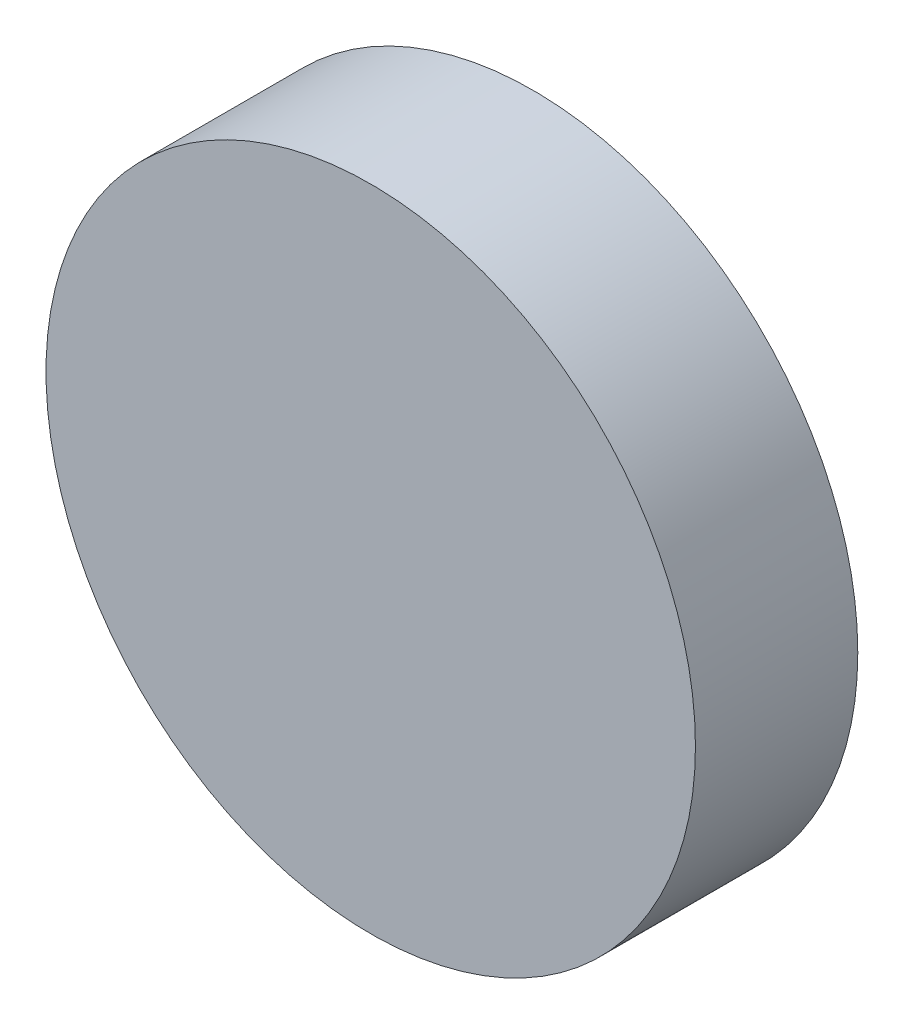
SolidWorks part; units mm, degrees
material "PET"
ref_plane "X-Y Datum" through (0, 0, 0) normal (0, 0, 1) x (1, 0, 0)
ref_plane "X-Z Datum" through (0, 0, 0) normal (0, 1, 0) x (1, 0, 0)
ref_plane "Y-Z Datum" through (0, 0, 0) normal (1, 0, 0) x (0, 0, -1)
sketch "Sketch1" plane through (0, 0, 0) normal (0, 0, 1) x (1, 0, 0)
  circle A0 centre (0, 0) radius 25.4
  circle A1 centre (0, 0) radius 23.876
  dimension "D1" = 50.8
  dimension "D2" = 47.752
extrude "Boss-Extrude1" add sketch "Sketch1" along normal blind 12.7
sketch "Sketch2" plane through (0, 0, 12.7) normal (0, 0, 1) x (1, 0, 0)
  circle A0 centre (0, 0) radius 23.876
extrude "Boss-Extrude2" add sketch "Sketch2" against normal blind 2.54
